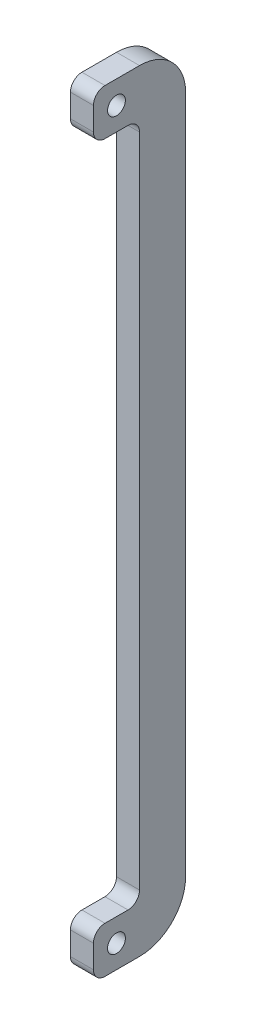
SolidWorks part; units mm, degrees
material "环氧树脂FR-4"
ref_plane "前视基准面" through (0, 0, 0) normal (0, 0, 1) x (1, 0, 0)
ref_plane "上视基准面" through (0, 0, 0) normal (0, 1, 0) x (1, 0, 0)
ref_plane "右视基准面" through (0, 0, 0) normal (1, 0, 0) x (0, 0, -1)
sketch "草图1" plane through (0, 0, 0) normal (1, 0, 0) x (0, 0, -1)
  line L1 (0, 8) -> (-8, 8)
  line L2 (0, 8) -> (0, 0) construction
  line L3 (0, 0) -> (-8, 0)
  line L4 (-8, 8) -> (-8, 0)
  line L5 (0, 8) -> (-8, 0) construction
  line L6 (0, 0) -> (-8, 8) construction
  line L7 (0, 0) -> (8, 0) construction
  line L11 (-8, 8) -> (-8, -59.01)
  line L12 (0, 0) -> (8, 0) construction
  line L15 (0, 0) -> (0, -126.02)
  line L20 (0, -126.02) -> (8, -126.02)
  line L21 (8, 0) -> (8, -126.02)
  line L22 (0, 0) -> (8, -126.02) construction
  line L23 (0, -126.02) -> (8, 0) construction
  line L24 (0, -126.02) -> (8, -126.02) construction
  line L25 (0, -126.02) -> (0, -118.02) construction
  line L26 (0, -118.02) -> (8, -118.02) construction
  line L27 (8, -126.02) -> (8, -118.02) construction
  line L28 (0, -126.02) -> (8, -118.02) construction
  line L29 (0, -118.02) -> (8, -126.02) construction
  line L30 (-8, -59.01) -> (0, -59.01)
  line L31 (0, -118.02) -> (-8, -118.02)
  line L32 (-8, -126.02) -> (-8, -118.02)
  line L33 (0, -126.02) -> (-8, -126.02)
  arc A0 (8, 0) -> (0, 8) centre (0, 0) ccw
  circle A2 centre (-4, 4) radius 1.55
  circle A7 centre (4, -122.02) radius 1.55
  arc A8 (8, -118.02) -> (0, -126.02) centre (0, -118.02) cw
  circle A9 centre (-4, -122.02) radius 1.55
  point P8 (-4, 4)
  point P10 (4, -63.01)
  point P16 (4, -122.02)
  dimension "D1" = 8
  dimension "D2" = 3.1
  dimension "D5" = 3.1
  dimension "D3" = 8
  dimension "D4" = 126.02
  dimension "D6" = 8
  dimension "D7" = 67.01
extrude "凸台-拉伸1" add sketch "草图1" along normal blind 4 contours A8 L21 A0 L1 L4 L3 L15 A2 | L33 L15 L31 L32 A9 | A7
fillet "圆角1" radius 2 6 edges at (2, -126.02, 8) (2, -118.02, 8) (2, -118.02, 0) (2, 0, 0) (2, 0, 8) (2, 8, 8)
